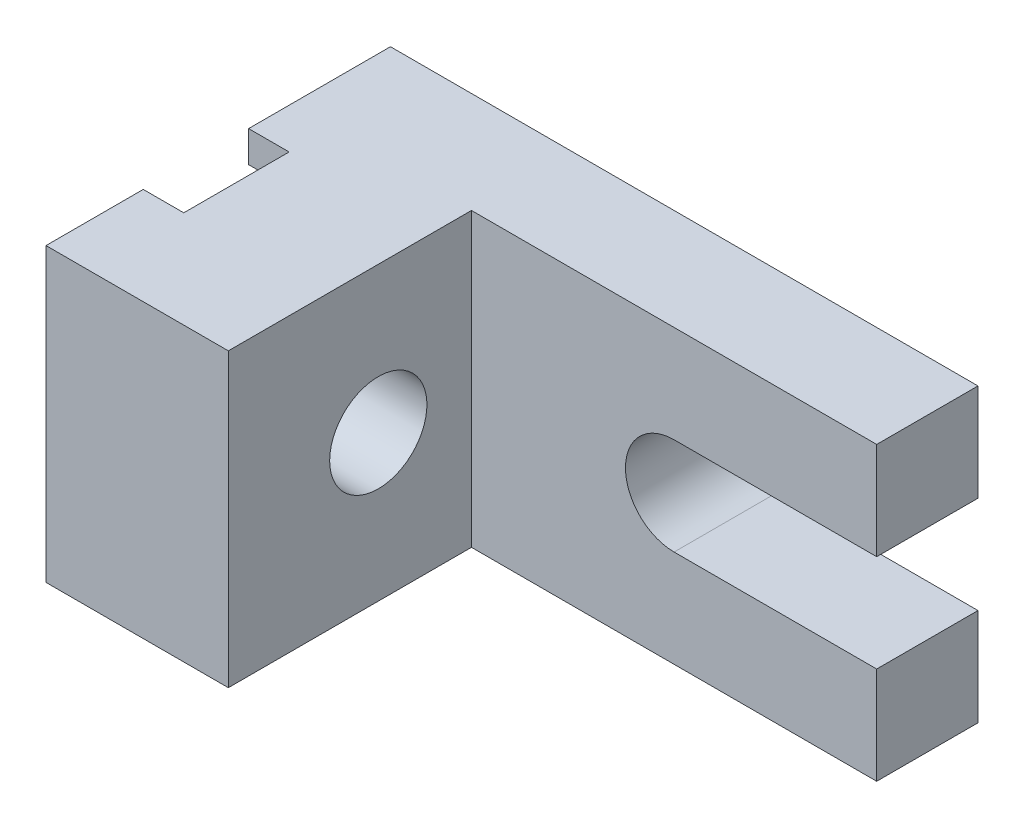
SolidWorks part; units mm, degrees
ref_plane "Front Plane" through (0, 0, 0) normal (0, 0, 1) x (1, 0, 0)
ref_plane "Top Plane" through (0, 0, 0) normal (0, 1, 0) x (1, 0, 0)
ref_plane "Right Plane" through (0, 0, 0) normal (1, 0, 0) x (0, 0, -1)
sketch "Sketch1" plane through (0, 0, 0) normal (0, 0, 1) x (1, 0, 0)
  line L1 (0, 0) -> (135, 0)
  line L2 (0, 0) -> (0, -72)
  line L3 (0, -72) -> (135, -72)
  line L4 (135, 0) -> (135, -72)
  dimension "D1" = 135
  dimension "D2" = 72
extrude "Boss-Extrude2" add sketch "Sketch1" along normal blind 25
sketch "Sketch2" plane through (0, -72, 0) normal (0, -1, 0) x (1, 0, 0)
  line L1 (0, 0) -> (60, 0)
  line L2 (0, 0) -> (0, 5)
  line L3 (0, 5) -> (60, 5)
  line L4 (60, 0) -> (60, 5)
  dimension "D1" = 60
  dimension "D2" = 5
extrude "Cut-Extrude1" cut sketch "Sketch2" against normal blind 72
sketch "Sketch3" plane through (0, 0, 0) normal (0, 0, 1) x (1, 0, 0)
  line L0 (135, -24) -> (85, -24)
  line L1 (135, -72) -> (135, 0) construction
  line L2 (85, -48) -> (135, -48)
  line L3 (135, -48) -> (135, -24)
  line L4 (0, -72) -> (135, -72) construction
  arc A0 (85, -24) -> (85, -48) centre (85, -36) ccw
  point P7 (0, 0)
  point P10 (135, -36)
  dimension "D1" = 24
  dimension "D2" = 12
  dimension "D3" = 50
extrude "Cut-Extrude2" cut sketch "Sketch3" along normal blind 153
sketch "Sketch4" plane through (0, 0, 0) normal (-1, 0, 0) x (0, 0, 1)
  line L1 (5, -72) -> (35, -72)
  line L2 (5, -72) -> (5, 0)
  line L3 (5, 0) -> (35, 0)
  line L4 (35, -72) -> (35, 0)
  dimension "D1" = 72
  dimension "D2" = 30
extrude "Boss-Extrude3" add sketch "Sketch4" along normal blind 10
sketch "Sketch7" plane through (-10, 0, 0) normal (-1, 0, 0) x (0, 0, 1)
  line L0 (25, -72) -> (35, -72) construction
  line L1 (5, 0) -> (0, 0)
  line L2 (5, 0) -> (5, -22)
  line L3 (5, -22) -> (0, -22)
  line L4 (0, 0) -> (0, -22)
  dimension "D1" = 5
  dimension "D2" = 50
extrude "Boss-Extrude4" add sketch "Sketch7" against normal blind 70
sketch "Sketch9" plane through (0, 0, 25) normal (0, 0, 1) x (1, 0, 0)
  line L0 (135, 0) -> (0, 0) construction
  line L1 (0, -72) -> (35, -72)
  line L2 (0, -72) -> (0, 0)
  line L3 (0, 0) -> (35, 0)
  line L4 (35, -72) -> (35, 0)
  dimension "D1" = 35
extrude "Boss-Extrude5" add sketch "Sketch9" along normal blind 60
sketch "Sketch10" plane through (0, -72, 0) normal (0, -1, 0) x (1, 0, 0)
  line L1 (0, 85) -> (-10, 85)
  line L2 (0, 85) -> (0, 61)
  line L3 (0, 61) -> (-10, 61)
  line L4 (-10, 85) -> (-10, 61)
  dimension "D1" = 24
  dimension "D2" = 10
extrude "Boss-Extrude6" add sketch "Sketch10" against normal blind 72
sketch "Sketch11" plane through (-10, 0, 0) normal (-1, 0, 0) x (0, 0, 1)
  line L0 (85, -36) -> (-49915, -36) construction
  line L1 (85, 0) -> (85, -72) construction
  line L2 (0, 0) -> (0, -22) construction
  line L3 (35, -7.7157) -> (35, -64.2843)
  line L4 (35, -72) -> (35, 0) construction
  line L5 (61, -10.6228) -> (61, -61.3772)
  line L6 (61, 0) -> (61, -72) construction
  arc A0 (61, -61.3772) -> (61, -10.6228) centre (45, -36) ccw
  arc A1 (35, -7.7157) -> (35, -64.2843) centre (45, -36) ccw
  point P4 (85, -36)
  dimension "D1" = 60
  dimension "D2" = 45
  dimension "D3" = 7.7157
extrude "Cut-Extrude3" cut sketch "Sketch11" against normal blind 10
sketch "Sketch12" plane through (0, 0, 0) normal (-1, 0, 0) x (0, 0, 1)
  line L0 (85, -36) -> (-49915, -36) construction
  line L1 (85, 0) -> (85, -72) construction
  line L3 (48, -72) -> (48, 49928) construction
  line L4 (61, -72) -> (35, -72) construction
  line L5 (61, 0) -> (35, 0) construction
  circle A0 centre (48, -36) radius 12
  point P4 (85, -36)
  point P9 (48, -72)
  point P12 (48, 0)
  dimension "D1" = 24
extrude "Cut-Extrude4" cut sketch "Sketch12" against normal blind 42
